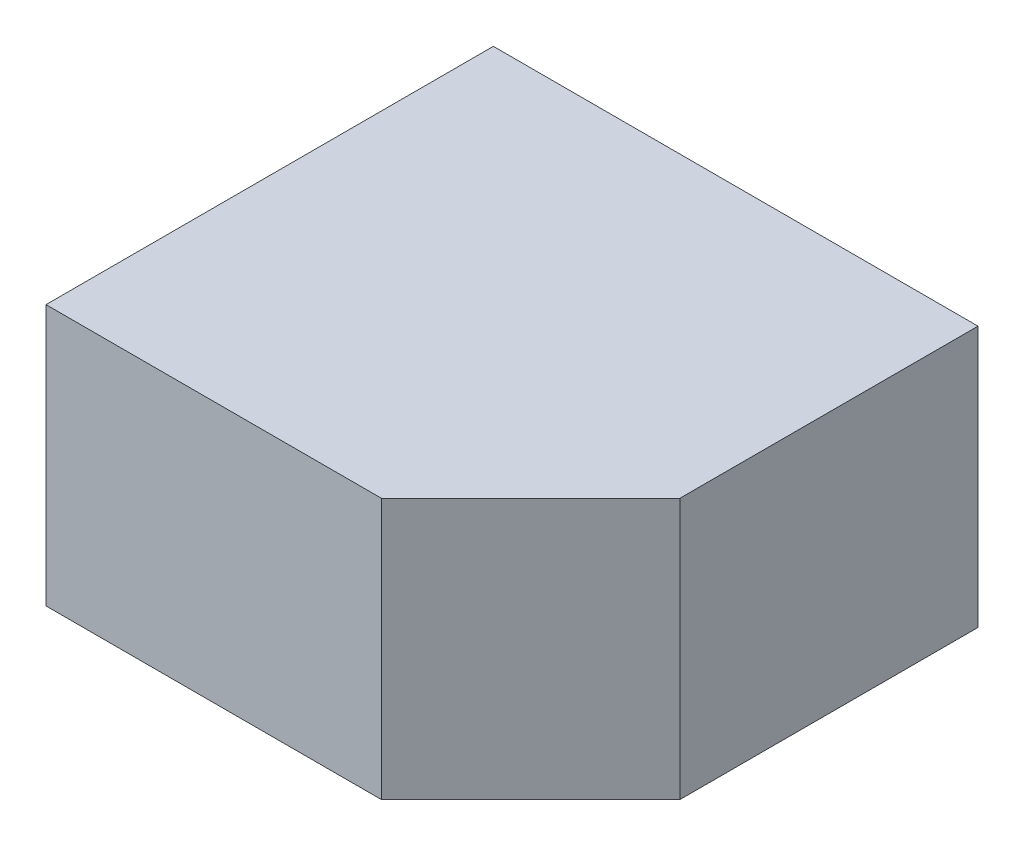
SolidWorks part; units mm, degrees
ref_plane "前视基准面" through (0, 0, 0) normal (0, 0, 1) x (1, 0, 0)
ref_plane "上视基准面" through (0, 0, 0) normal (0, 1, 0) x (1, 0, 0)
ref_plane "右视基准面" through (0, 0, 0) normal (1, 0, 0) x (0, 0, -1)
sketch "草图1" plane through (0, 0, 0) normal (0, 0, 1) x (1, 0, 0)
  line L1 (-251.5, 279) -> (251.5, 279)
  line L2 (-251.5, 279) -> (-251.5, -279)
  line L3 (-251.5, -279) -> (251.5, -279)
  line L4 (251.5, 279) -> (251.5, -279)
  line L5 (-251.5, 279) -> (251.5, -279) construction
  line L6 (-251.5, -279) -> (251.5, 279) construction
  point P0 (0, 0)
  dimension "D1" = 558
  dimension "D2" = 503
extrude "凸台-拉伸1" add sketch "草图1" along normal blind 865
sketch "草图2" plane through (251.5, 0, 0) normal (1, 0, 0) x (0, 0, -1)
  line L0 (0, -279) -> (0, 279) construction
  line L1 (100, 199) -> (-100, 199)
  line L2 (100, 199) -> (100, -199)
  line L3 (100, -199) -> (-100, -199)
  line L4 (-100, 199) -> (-100, -199)
  line L5 (100, 199) -> (-100, -199) construction
  line L6 (100, -199) -> (-100, 199) construction
  line L7 (-865, -279) -> (0, -279) construction
  point P0 (0, 0)
  dimension "D1" = 100
  dimension "D2" = 80
extrude "切除-拉伸1" cut sketch "草图2" against normal through all
sketch "草图3" plane through (251.5, 0, 0) normal (1, 0, 0) x (0, 0, -1)
  line L0 (-865, -279) -> (0, -279) construction
  line L1 (-100, -353) -> (-6, -353)
  line L2 (-100, -353) -> (-100, -205)
  line L3 (-100, -205) -> (-6, -205)
  line L4 (-6, -353) -> (-6, -205)
  line L5 (-100, -353) -> (-6, -205) construction
  line L6 (-100, -205) -> (-6, -353) construction
  line L7 (-100, 199) -> (-100, -199) construction
  line L8 (0, -279) -> (0, -199) construction
  line L9 (-100, -199) -> (0, -199) construction
  point P0 (-53, -279)
  dimension "D1" = 6
  dimension "D2" = 6
extrude "切除-拉伸2" cut sketch "草图3" against normal through all
mirror "镜向1" about plane through (0, 0, 0) normal (0, 1, 0) of "切除-拉伸2"
sketch "草图4" plane through (0, 0, 0) normal (0, 0, -1) x (-1, 0, 0)
  line L0 (251.5, -279) -> (-251.5, -279) construction
  line L1 (251.5, -479) -> (-48.5, -479)
  line L2 (251.5, -479) -> (251.5, -1079)
  line L3 (251.5, -1079) -> (-48.5, -1079)
  line L4 (-48.5, -479) -> (-48.5, -1079)
  dimension "D1" = 600
  dimension "D2" = 300
  dimension "D3" = 200
extrude "凸台-拉伸2" [suppressed] add sketch "草图4" against normal blind 865 separate body
sketch "草图5" plane through (0, 0, 0) normal (0, 0, -1) x (-1, 0, 0)
  line L0 (251.5, 279) -> (251.5, -279) construction
  line L1 (251.5, 479) -> (-398.5, 479)
  line L2 (251.5, 479) -> (251.5, 829)
  line L3 (251.5, 829) -> (-398.5, 829)
  line L4 (-398.5, 479) -> (-398.5, 829)
  line L5 (-251.5, 279) -> (251.5, 279) construction
  dimension "D1" = 650
  dimension "D2" = 350
  dimension "D3" = 200
extrude "凸台-拉伸3" add sketch "草图5" against normal blind 600 separate body
chamfer "倒角1" distance 200 angle 45 1 edges at (398.5, 654, 600)
sketch "草图6" plane through (0, 0, 0) normal (0, 0, -1) x (-1, 0, 0)
  line L0 (251.5, 479) -> (251.5, 829) construction
  line L1 (251.5, 1129) -> (-748.5, 1129)
  line L2 (251.5, 1129) -> (251.5, -3701)
  line L3 (251.5, -3701) -> (-748.5, -3701)
  line L4 (-748.5, 1129) -> (-748.5, -3701)
  line L5 (251.5, 829) -> (-398.5, 829) construction
  dimension "D1" = 300
  dimension "D2" = 1000
  dimension "D3" = 4830
extrude "凸台-拉伸4" add sketch "草图6" along normal blind 30 separate body
sketch "草图7" plane through (748.5, 0, 0) normal (1, 0, 0) x (0, 0, -1)
  line L1 (0, 1129) -> (625.7748, 1129)
  line L2 (0, 1129) -> (0, -3888.8571)
  line L3 (0, -3888.8571) -> (625.7748, -3888.8571)
  line L4 (625.7748, 1129) -> (625.7748, -3888.8571)
extrude "切除-拉伸3" cut sketch "草图7" against normal through all
sketch "草图8" plane through (251.5, 0, 0) normal (1, 0, 0) x (0, 0, -1)
  line L1 (-1125.8571, -878.2242) -> (198.7178, -878.2242)
  line L2 (-1125.8571, -878.2242) -> (-1125.8571, 348.5128)
  line L3 (-1125.8571, 348.5128) -> (198.7178, 348.5128)
  line L4 (198.7178, -878.2242) -> (198.7178, 348.5128)
extrude "切除-拉伸4" cut sketch "草图8" against normal through all
equation "\"零件重量\"= \"SW-质量\""
